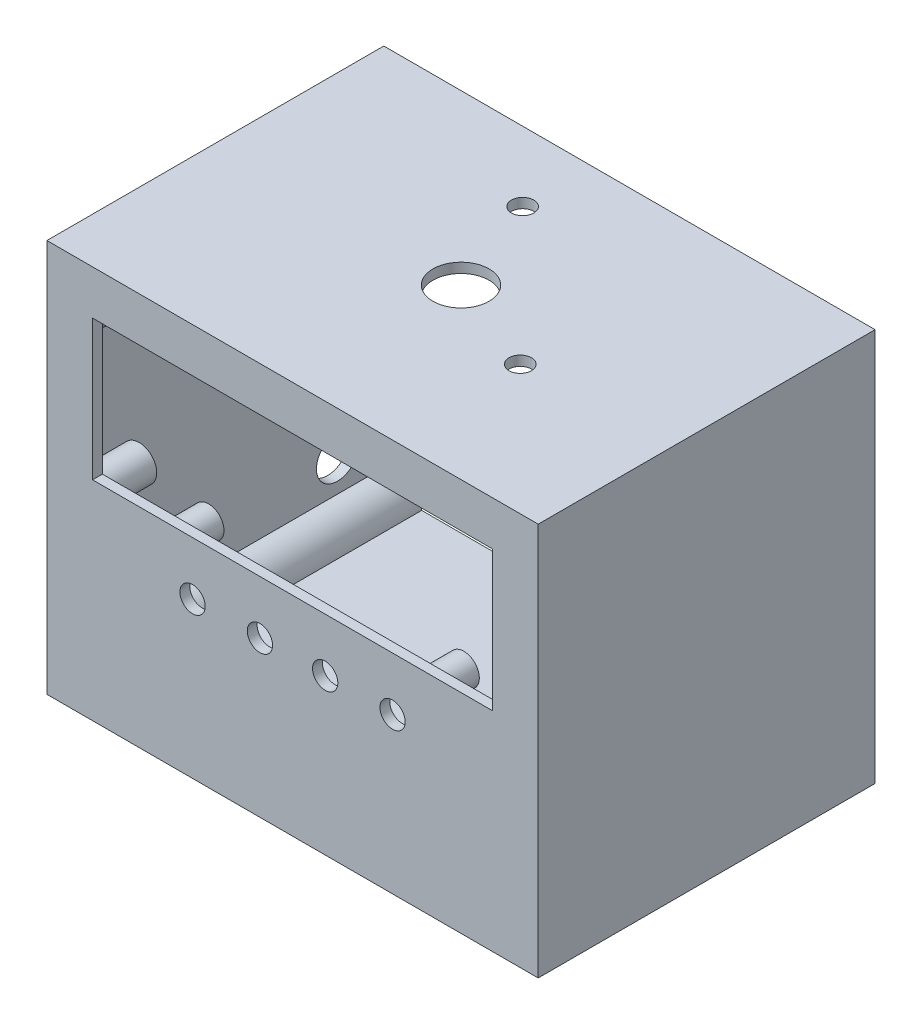
SolidWorks part; units mm, degrees
ref_plane "Front Plane" through (0, 0, 0) normal (0, 0, 1) x (1, 0, 0)
ref_plane "Top Plane" through (0, 0, 0) normal (0, 1, 0) x (1, 0, 0)
ref_plane "Right Plane" through (0, 0, 0) normal (1, 0, 0) x (0, 0, -1)
sketch "Sketch1" plane through (0, 0, 0) normal (0, 0, 1) x (1, 0, 0)
  line L1 (-44.45, 35.56) -> (44.45, 35.56)
  line L2 (-44.45, 35.56) -> (-44.45, -35.56)
  line L3 (-44.45, -35.56) -> (44.45, -35.56)
  line L4 (44.45, 35.56) -> (44.45, -35.56)
  line L5 (-44.45, 35.56) -> (44.45, -35.56) construction
  line L6 (-44.45, -35.56) -> (44.45, 35.56) construction
  point P0 (0, 0)
  dimension "D1" = 88.9
  dimension "D2" = 71.12
extrude "Boss-Extrude1" add sketch "Sketch1" along normal blind 60.96
sketch "Sketch2" plane through (0, 0, 0) normal (0, 0, -1) x (-1, 0, 0)
  line L8 (-42.672, 33.782) -> (-42.672, -33.782)
  line L9 (-42.672, -33.782) -> (42.672, -33.782)
  line L10 (42.672, -33.782) -> (42.672, 33.782)
  line L11 (42.672, 33.782) -> (-42.672, 33.782)
  line L12 (-42.672, 33.782) -> (-42.672, -33.782)
  line L13 (-42.672, -33.782) -> (42.672, -33.782)
  line L14 (42.672, -33.782) -> (42.672, 33.782)
  line L15 (42.672, 33.782) -> (-42.672, 33.782)
  dimension "D1" = 1.778
extrude "Cut-Extrude1" cut sketch "Sketch2" against normal blind 59.182
sketch "Sketch3" plane through (0, 0, 60.96) normal (0, 0, 1) x (1, 0, 0)
  circle A0 centre (-18.0975, -7.4676) radius 2.286
  circle A1 centre (-5.9055, -7.4676) radius 2.286
  circle A2 centre (5.9055, -7.4676) radius 2.286
  circle A3 centre (18.0975, -7.4676) radius 2.286
  dimension "D1" = 4.572
extrude "Cut-Extrude2" cut sketch "Sketch3" against normal blind 5.08
sketch "Sketch4" plane through (0, 0, 59.182) normal (0, 0, -1) x (-1, 0, 0)
  circle A0 centre (-23.1013, -1.778) radius 2.794
  circle A1 centre (23.1013, -1.778) radius 2.794
  circle A2 centre (23.1013, -30.0228) radius 2.794
  circle A3 centre (-23.1013, -30.0228) radius 2.794
  dimension "D1" = 5.588
extrude "Boss-Extrude2" add sketch "Sketch4" along normal up to vertex (6.1214 mm away)
sketch "Sketch5" plane through (0, 0, 53.0606) normal (0, 0, -1) x (-1, 0, 0)
  circle A0 centre (-23.1013, -1.778) radius 1.27
  circle A1 centre (23.1013, -1.778) radius 1.27
  circle A2 centre (23.1013, -30.0228) radius 1.27
  circle A3 centre (-23.1013, -30.0228) radius 1.27
  dimension "D1" = 2.54
extrude "Cut-Extrude3" cut sketch "Sketch5" against normal blind 3.81
sketch "Sketch7" plane through (0, 0, 60.96) normal (0, 0, 1) x (1, 0, 0)
  line L0 (-36.195, 27.5374) -> (36.195, 27.5374)
  line L5 (36.195, 27.5374) -> (36.195, 2.1882)
  line L6 (-36.195, 2.1882) -> (36.195, 2.1882)
  line L7 (-36.195, 27.5374) -> (-36.195, 2.1882)
extrude "Cut-Extrude5" cut sketch "Sketch7" against normal blind 4.699
sketch "Sketch8" plane through (0, 0, 59.182) normal (0, 0, -1) x (-1, 0, 0)
  circle A0 centre (-37.5285, 30.5435) radius 3.175
  circle A1 centre (37.5285, 30.5435) radius 3.175
  circle A2 centre (37.5285, -0.6985) radius 3.175
  circle A3 centre (-37.5285, -0.6985) radius 3.175
  dimension "D1" = 6.35
extrude "Boss-Extrude3" add sketch "Sketch8" along normal up to vertex (7.9996 mm away)
sketch "Sketch9" plane through (0, 0, 51.1824) normal (0, 0, -1) x (-1, 0, 0)
  circle A0 centre (-37.5285, 30.5435) radius 1.27
  circle A1 centre (37.5285, 30.5435) radius 1.27
  circle A2 centre (37.5285, -0.6985) radius 1.27
  circle A3 centre (-37.5285, -0.6985) radius 1.27
  dimension "D1" = 2.54
extrude "Cut-Extrude6" cut sketch "Sketch9" against normal blind 3.81
sketch "Sketch10" plane through (0, 35.56, 0) normal (0, 1, 0) x (1, 0, 0)
  line L0 (0, 0) -> (0, -60.96) construction
  line L1 (44.45, -60.96) -> (-44.45, -60.96) construction
  line L2 (-44.45, -30.48) -> (44.45, -30.48) construction
  line L3 (-44.45, -60.96) -> (-44.45, 0) construction
  line L4 (44.45, -60.96) -> (44.45, 0) construction
sketch "Sketch11" plane through (0, 35.56, 0) normal (0, 1, 0) x (1, 0, 0)
  line L0 (0, 0) -> (0, -60.96) construction
  circle A0 centre (-6.732, -12.5948) radius 2.032
  circle A1 centre (17.765, -37.5232) radius 2.032
  circle A2 centre (0, -30.48) radius 5.08
  dimension "D1" = 10.16
extrude "Cut-Extrude7" cut sketch "Sketch11" against normal blind 5.08
sketch "Sketch12" plane through (-44.45, 0, 0) normal (-1, 0, 0) x (0, 0, 1)
  line L0 (0, 35.56) -> (0, -35.56) construction
  line L1 (60.96, -35.56) -> (0, -35.56) construction
  circle A0 centre (10.16, -22.86) radius 3.81
  dimension "D1" = 7.62
  dimension "D2" = 10.16
  dimension "D3" = 12.7
extrude "Cut-Extrude8" cut sketch "Sketch12" against normal blind 3.302
sketch "Sketch13" plane through (0, 0, 59.182) normal (0, 0, -1) x (-1, 0, 0)
  line L0 (42.672, 25.3466) -> (42.672, 19.2099)
  line L2 (44.45, -29.0233) -> (44.45, -35.56)
  line L4 (-42.672, 25.3466) -> (-42.672, 19.2099)
  line L5 (-42.672, 33.782) -> (-42.672, -33.782) construction
  line L6 (0, 0) -> (0, 11.499) construction
  line L7 (44.45, -35.56) -> (37.9133, -35.56)
  line L8 (-44.45, -29.0233) -> (-44.45, -35.56)
  line L9 (-44.45, -35.56) -> (-44.45, 35.56) construction
  line L10 (-44.45, -35.56) -> (-37.9133, -35.56)
  line L11 (44.45, -35.56) -> (-44.45, -35.56) construction
  arc A0 (-42.672, 19.2099) -> (-42.672, 25.3466) centre (-43.488, 22.2783) ccw
  arc A1 (42.672, 19.2099) -> (42.672, 25.3466) centre (43.488, 22.2783) cw
  arc A3 (37.9133, -35.56) -> (44.45, -29.0233) centre (42.672, -33.782) cw
  arc A5 (-37.9133, -35.56) -> (-44.45, -29.0233) centre (-42.672, -33.782) ccw
  dimension "D1" = 6.35
  dimension "D2" = 5.08
extrude "Boss-Extrude4" add sketch "Sketch13" along normal up to vertex (59.182 mm away)
sketch "Sketch14" plane through (0, 0, 0) normal (0, 0, -1) x (-1, 0, 0)
  line L1 (-44.45, -35.56) -> (-44.45, 35.56) construction
  line L2 (44.45, -35.56) -> (-44.45, -35.56) construction
  line L3 (0, 0) -> (0, 11.3924) construction
  circle A0 centre (-42.345, 22.2783) radius 1.27
  circle A1 centre (-41.275, -32.385) radius 1.27
  circle A2 centre (41.275, -32.385) radius 1.27
  circle A3 centre (42.345, 22.2783) radius 1.27
  arc A4 (-42.672, 19.2099) -> (-42.672, 25.3466) centre (-43.488, 22.2783) ccw construction
  point P21 (-40.313, 22.2783)
  dimension "D1" = 2.54
  dimension "D2" = 2.54
  dimension "D3" = 3.175
  dimension "D4" = 3.175
  dimension "D5" = 2.032
extrude "Cut-Extrude9" cut sketch "Sketch14" against normal blind 3.81
